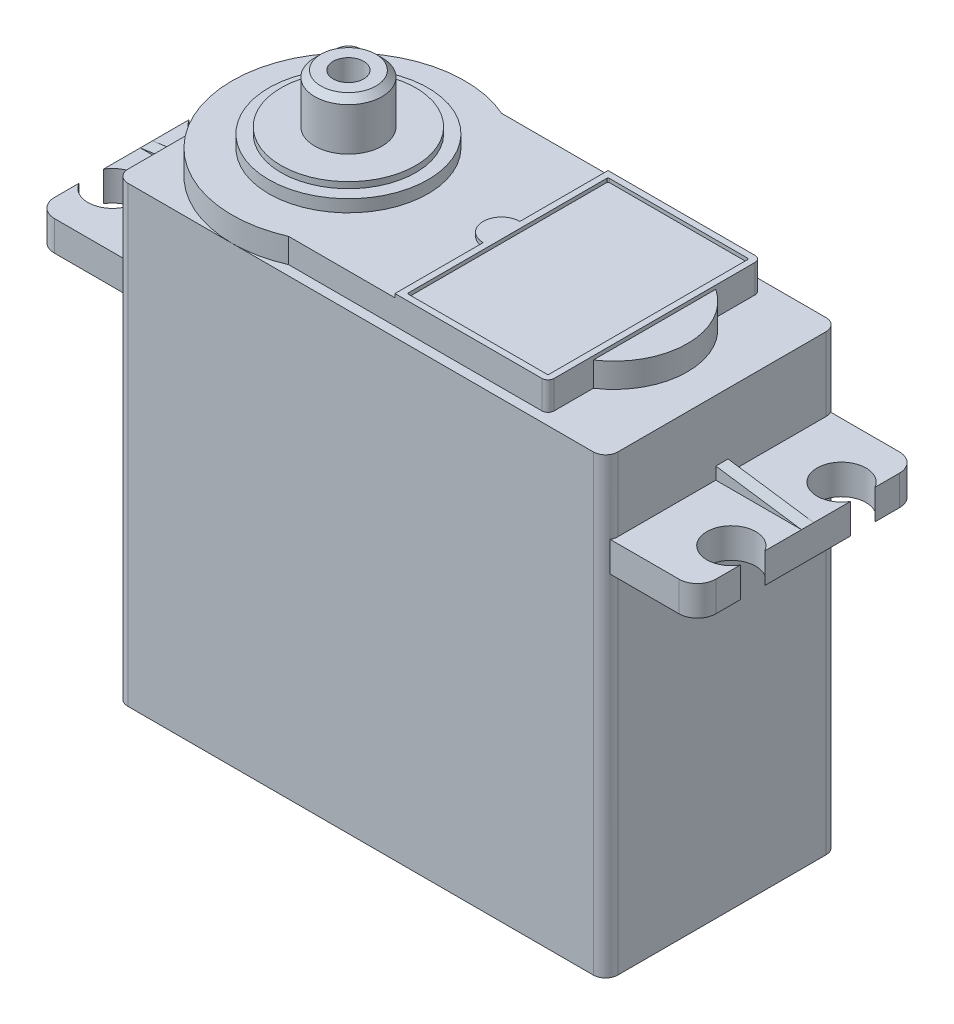
SolidWorks part; units mm, degrees
material "ABS"
ref_plane "Alzado" through (0, 0, 0) normal (0, 0, 1) x (1, 0, 0)
ref_plane "Planta" through (0, 0, 0) normal (0, 1, 0) x (1, 0, 0)
ref_plane "Vista lateral" through (0, 0, 0) normal (1, 0, 0) x (0, 0, -1)
sketch "Croquis1" plane through (0, 0, 0) normal (0, 1, 0) x (1, 0, 0)
  line L1 (1, 0) -> (39, 0)
  line L2 (0, 1) -> (0, 18)
  line L3 (1, 19) -> (39, 19)
  line L4 (40, 1) -> (40, 18)
  arc A0 (39, 0) -> (40, 1) centre (39, 1) ccw
  arc A1 (1, 0) -> (0, 1) centre (1, 1) cw
  arc A2 (39, 19) -> (40, 18) centre (39, 18) cw
  arc A3 (0, 18) -> (1, 19) centre (1, 18) cw
  point P7 (40, 0)
  point P10 (0, 0)
  point P15 (0, 19)
  dimension "D3" = 1
  dimension "D1" = 19
  dimension "D2" = 40
extrude "Saliente-Extruir1" add sketch "Croquis1" along normal blind 37
sketch "Croquis2" plane through (0, 37, 0) normal (0, 1, 0) x (1, 0, 0)
  line L0 (0, 18) -> (0, 1) construction
  line L1 (39, 19) -> (1, 19) construction
  line L2 (40, 1) -> (40, 18) construction
  line L3 (13.3158, 18.2) -> (34.5, 18.2)
  line L5 (13.3158, 0.8) -> (34.5, 0.8)
  line L6 (34.5, 18.2) -> (34.5, 14.5)
  line L8 (34.5, 4.5) -> (34.5, 0.8)
  arc A0 (13.3158, 18.2) -> (13.3158, 0.8) centre (9.5, 9.5) ccw
  arc A1 (34.5, 4.5) -> (34.5, 14.5) centre (31.1834, 9.5) ccw
  dimension "D1" = 19
  dimension "D6" = 12
  dimension "D2" = 17.4
  dimension "D3" = 5.5
  dimension "D4" = 21.1842
  dimension "D5" = 10
extrude "Saliente-Extruir2" add sketch "Croquis2" along normal blind 2
sketch "Croquis3" plane through (0, 39, 0) normal (0, 1, 0) x (1, 0, 0)
  circle A0 centre (9.5, 9.5) radius 6.5
  dimension "D1" = 13
extrude "Saliente-Extruir3" add sketch "Croquis3" along normal blind 1
sketch "Croquis4" plane through (0, 40, 0) normal (0, 1, 0) x (1, 0, 0)
  circle A0 centre (9.5, 9.5) radius 5.5
  dimension "D1" = 11
extrude "Saliente-Extruir4" add sketch "Croquis4" along normal blind 0.5
sketch "Croquis5" plane through (0, 40.5, 0) normal (0, 1, 0) x (1, 0, 0)
  circle A0 centre (9.5, 9.5) radius 2.75
  dimension "D1" = 5.5
extrude "Saliente-Extruir5" add sketch "Croquis5" along normal blind 4
sketch "Croquis7" plane through (0, 39, 0) normal (0, 1, 0) x (1, 0, 0)
  line L0 (34.5, 18.2) -> (13.3158, 18.2) construction
  line L1 (34.5, 0.8) -> (22, 0.8)
  line L2 (34.5, 0.8) -> (34.5, 18.2)
  line L3 (34.5, 18.2) -> (22, 18.2)
  line L4 (22, 0.8) -> (22, 8)
  line L5 (22.5, 1.3) -> (22.5, 17.7)
  line L6 (34, 17.7) -> (22.5, 17.7)
  line L7 (34, 1.3) -> (34, 17.7)
  line L8 (34, 1.3) -> (22.5, 1.3)
  line L10 (22, 11) -> (22, 18.2)
  line L11 (22, 0.8) -> (22, 18.2) construction
  arc A0 (22, 11) -> (22, 8) centre (22, 9.5) ccw
  dimension "D3" = 1.5
  dimension "D4" = 8.7
  dimension "D1" = 12.5
  dimension "D2" = 0.5
extrude "Saliente-Extruir6" add sketch "Croquis7" along normal blind 0.3
fillet "Redondeo1" radius 0.1 4 edges at (22.5, 39.15, -1.3) (34, 39.15, -1.3) (34, 39.15, -17.7) (22.5, 39.15, -17.7)
fillet "Redondeo2" radius 0.5 2 edges at (34.5, 38.15, -0.8) (34.5, 38.15, -18.2)
sketch "Croquis8" plane through (0, 37, 0) normal (0, 1, 0) x (1, 0, 0)
  line L0 (40, 1) -> (40, 18) construction
  line L1 (40, 1) -> (40, 18)
  line L2 (39, 19) -> (9.5, 19) construction
  line L3 (39.866, 18.5) -> (45.5, 18.5)
  line L5 (39.866, 0.5) -> (45.5, 0.5)
  line L6 (47, 17) -> (47, 15)
  line L7 (47, 13) -> (47, 6)
  line L8 (40, 9.5) -> (47, 9.5) construction
  line L9 (47, 4) -> (47, 2)
  line L10 (0, 18) -> (40, 18) construction
  line L11 (20, 19) -> (20, 0) construction
  line L12 (9.5, 0) -> (39, 0) construction
  line L13 (-7, 17) -> (-7, 15)
  line L14 (0.134, 18.5) -> (-5.5, 18.5)
  line L15 (0, 1) -> (0, 18)
  line L16 (0.134, 0.5) -> (-5.5, 0.5)
  line L17 (-7, 4) -> (-7, 2)
  line L18 (-7, 13) -> (-7, 6)
  arc A0 (39, 0) -> (40, 1) centre (39, 1) ccw construction
  arc A1 (40, 18) -> (39, 19) centre (39, 18) ccw construction
  arc A2 (39.866, 0.5) -> (40, 1) centre (39, 1) ccw
  arc A3 (40, 18) -> (39.866, 18.5) centre (39, 18) ccw
  arc A4 (47, 15) -> (47, 13) centre (45.2679, 14) ccw
  arc A6 (47, 4) -> (47, 6) centre (45.2679, 5) cw
  arc A7 (45.5, 0.5) -> (47, 2) centre (45.5, 2) ccw
  arc A8 (45.5, 18.5) -> (47, 17) centre (45.5, 17) cw
  arc A9 (-7, 15) -> (-7, 13) centre (-5.2679, 14) cw
  arc A10 (-5.5, 18.5) -> (-7, 17) centre (-5.5, 17) ccw
  arc A11 (0, 18) -> (0.134, 18.5) centre (1, 18) cw
  arc A12 (0.134, 0.5) -> (0, 1) centre (1, 1) cw
  arc A13 (-5.5, 0.5) -> (-7, 2) centre (-5.5, 2) cw
  arc A14 (-7, 4) -> (-7, 6) centre (-5.2679, 5) ccw
  point P25 (47, 18.5)
  point P31 (20, 18)
  dimension "D4" = 4
  dimension "D5" = 1.5
  dimension "D1" = 7
  dimension "D2" = 18
  dimension "D3" = 2
  dimension "D6" = 5
  dimension "D7" = 7.134
extrude "Saliente-Extruir7" add sketch "Croquis8" against normal blind 2.45 from offset 6 offset against normal yes
ref_plane "Plano1" through (0, 0, -9.5) normal (0, 0, 1) x (1, 0, 0)
sketch "Croquis10" plane through (0, 0, -9.5) normal (0, 0, 1) x (1, 0, 0)
  line L0 (47, 31) -> (40, 32)
  line L1 (40, 37) -> (40, 31) construction
  line L2 (40, 32) -> (40, 31)
  line L3 (40, 31) -> (47, 31)
  line L4 (20, 0) -> (20, 37) construction
  line L5 (1, 0) -> (39, 0) construction
  line L6 (9.5, 37) -> (39, 37) construction
  line L7 (0, 32) -> (0, 31)
  line L8 (-7, 31) -> (0, 32)
  line L9 (0, 31) -> (-7, 31)
  dimension "D1" = 1
extrude "Saliente-Extruir8" add sketch "Croquis10" along normal mid plane 1
sketch "Croquis11" plane through (0, 0, 0) normal (1, 0, 0) x (0, 0, -1)
  line L0 (1, 0) -> (18, 0) construction
  line L1 (6.5, 5.5) -> (12.5, 5.5)
  line L2 (6.5, 5.5) -> (6.5, 3)
  line L3 (6.5, 3) -> (12.5, 3)
  line L4 (12.5, 5.5) -> (12.5, 3)
  point P4 (9.5, 3)
  point P7 (9.5, 0)
  dimension "D1" = 6
  dimension "D2" = 2.5
  dimension "D3" = 3
extrude "Saliente-Extruir9" add sketch "Croquis11" against normal blind 5 draft 8
sketch "Croquis12" plane through (0, 44.5, 0) normal (0, 1, 0) x (1, 0, 0)
  circle A0 centre (9.5, 9.5) radius 1.25
  dimension "D1" = 2.5
extrude "Cortar-Extruir1" cut sketch "Croquis12" against normal blind 5
chamfer "Chaflán1" distance 0.5 angle 45 1 edges at (9.5, 44.5, -6.75)
